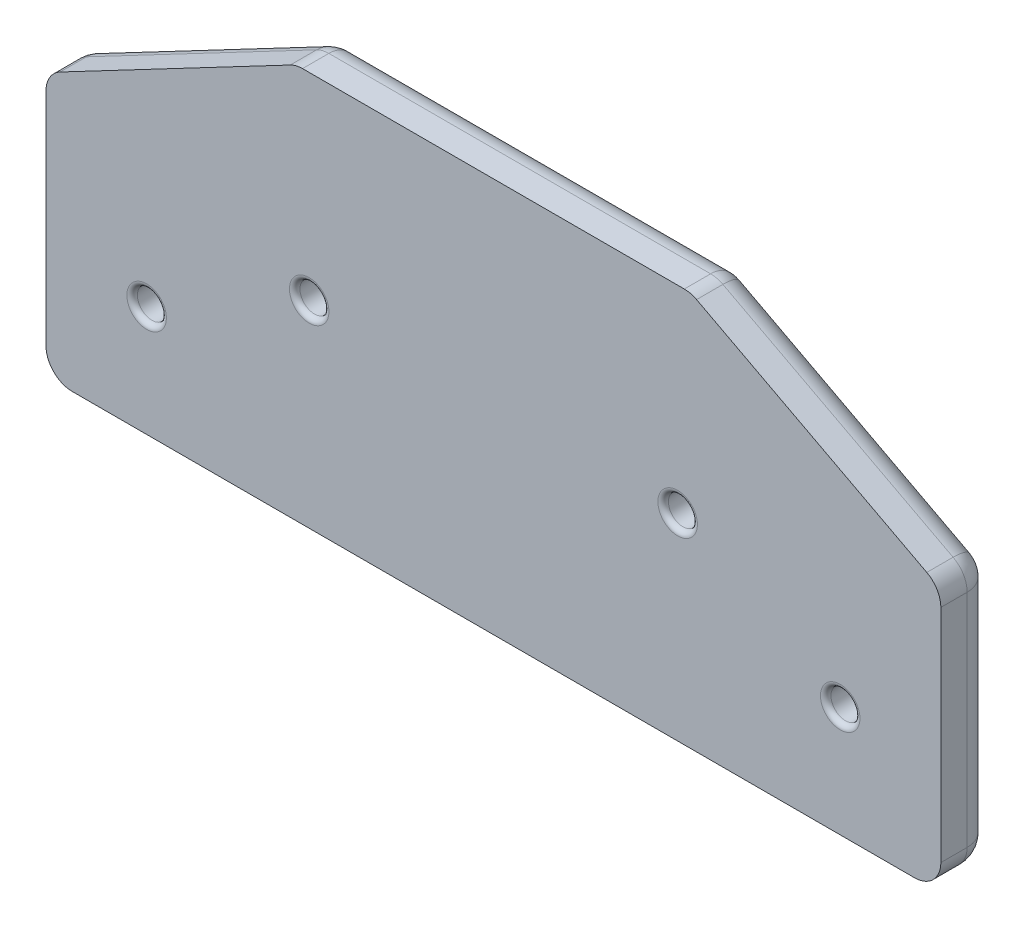
SolidWorks part; units mm, degrees
material "ABS"
ref_plane "Front Plane" through (0, 0, 0) normal (0, 0, 1) x (1, 0, 0)
ref_plane "Top Plane" through (0, 0, 0) normal (0, 1, 0) x (1, 0, 0)
ref_plane "Right Plane" through (0, 0, 0) normal (1, 0, 0) x (0, 0, -1)
sketch "Sketch2" plane through (0, 0, 0) normal (0, 0, 1) x (1, 0, 0)
  line L9 (0, 0) -> (170, 0)
  line L10 (170, 0) -> (170, 50)
  line L11 (170, 50) -> (122.5, 75)
  line L12 (122.5, 75) -> (47.5, 75)
  line L13 (47.5, 75) -> (0, 50)
  line L14 (0, 50) -> (0, 0)
  line L15 (0, 50) -> (170, 50)
  line L16 (85, 75) -> (85, 0) construction
  line L22 (47.5, 75) -> (47.5, 50)
  line L27 (122.5, 75) -> (122.5, 50)
  line L30 (50, 37.5) -> (120, 37.5) construction
  circle A0 centre (50, 37.5) radius 2.75
  circle A1 centre (120, 37.5) radius 2.75
  circle A3 centre (150.8824, 21.0294) radius 2.75
  circle A5 centre (19.1176, 21.0294) radius 2.75
  point P20 (85, 37.5)
  point P21 (85, 37.5)
  line M18 (170, 0) -> (170, 10)
  line M19 (170, 10) -> (0, 10)
  line M20 (0, 10) -> (0, 0)
  line M21 (0, 0) -> (47.5, 0)
  line M25 (57.5, 0) -> (112.5, 0)
  line M29 (122.5, 0) -> (170, 0)
  dimension "D7" = 70
  dimension "D8" = 5.5
  dimension "D9" = 5.5
  dimension "D10" = 35
  dimension "D11" = 35
  dimension "D12" = 16.4706
  dimension "D5" = 5.5
  dimension "D6" = 5.5
  dimension "D1" = 75
  dimension "D2" = 25
  dimension "D3" = 170
  dimension "D4" = 75
extrude "Boss-Extrude1" add sketch "Sketch2" along normal blind 10 contours L15 L14 L10 A5 A3 A1 A0 M19 | L22 L13 L15 | L27 L12 L22 L15 | L11 L27 L15 | L9 M21 M25 M29 M18 M19 M20
fillet "Fillet1" radius 5 6 edges at (170, 0, 5) (0, 0, 5) (170, 50, 5) (122.5, 75, 5) (47.5, 75, 5) (0, 50, 5)
fillet "Fillet2" radius 5 12 edges at (0.7196, 49.5656, 0) (24.539, 62.9153, 0) (47.5361, 74.854, 0) (85, 75, 0) (122.4639, 74.854, 0) (145.461, 62.9153, 0) (169.2804, 49.5656, 0) (170, 25.9907, 0) (168.5355, 1.4645, 0) (85, 0, 0) (1.4645, 1.4645, 0) (0, 25.9907, 0)
fillet "Fillet3" radius 1 8 edges at (21.8676, 21.0294, 10) (21.8676, 21.0294, 0) (52.75, 37.5, 10) (52.75, 37.5, 0) (122.75, 37.5, 10) (122.75, 37.5, 0) (153.6324, 21.0294, 10) (153.6324, 21.0294, 0)
